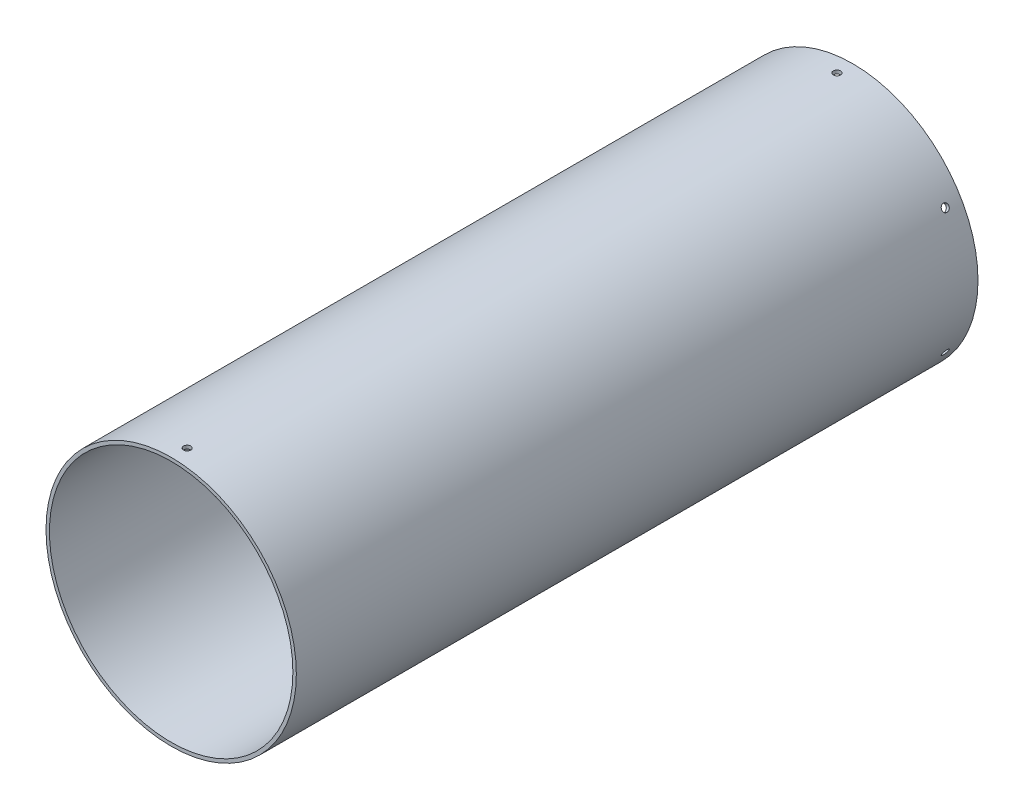
SolidWorks part; units mm, degrees
material "A-Glass Fiber"
ref_plane "Front Plane" through (0, 0, 0) normal (0, 0, 1) x (1, 0, 0)
ref_plane "Top Plane" through (0, 0, 0) normal (0, 1, 0) x (1, 0, 0)
ref_plane "Right Plane" through (0, 0, 0) normal (1, 0, 0) x (0, 0, -1)
sketch "Sketch1" plane through (0, 0, 0) normal (0, 0, 1) x (1, 0, 0)
  circle A0 centre (0, 0) radius 76.2
  circle A1 centre (0, 0) radius 78.359
  dimension "D1" = 156.718
  dimension "D2" = 152.4
extrude "Boss-Extrude1" add sketch "Sketch1" along normal blind 426.75
sketch "Sketch4" plane through (0, 0, 0) normal (0, 1, 0) x (1, 0, 0)
  line L0 (78.359, 0) -> (-78.359, 0) construction
  point P0 (0, -10)
  dimension "D1" = 10
hole_wizard "M4 Clearance Hole2" positions "Sketch4" profile "Sketch5" hole size "M4" standard "ANSI Metric"
sketch "Sketch5" plane through (0, 0, 10) normal (1, 0, 0) x (0, 0, 1)
  line L0 (0, 0) -> (0, 78.359)
  line L1 (0, 78.359) -> (2.25, 78.359)
  line L2 (2.25, 78.359) -> (2.25, 0)
  line L5 (2.25, 0) -> (0, 0)
  line L11 (0, -6.35) -> (0, 107.95) construction
  dimension "Thru Hole Dia." = 4.5
  dimension "Thru Hole Depth" = 78.359
pattern_circular "CirPattern1" count 6 over 360 about axis through (0, 0, 426.75) along (0, 0, -1) of "M4 Clearance Hole2"
sketch "Sketch6" plane through (0, 0, 0) normal (0, 1, 0) x (1, 0, 0)
  line L0 (-78.359, -426.75) -> (78.359, -426.75) construction
  point P0 (0, -416.75)
  dimension "D1" = 10
hole_wizard "M4 Clearance Hole3" positions "Sketch6" profile "Sketch7" hole size "M4" standard "ANSI Metric"
sketch "Sketch7" plane through (0, 0, 416.75) normal (1, 0, 0) x (0, 0, -1)
  line L0 (0, 0) -> (0, 78.359)
  line L1 (0, 78.359) -> (2.25, 78.359)
  line L2 (2.25, 78.359) -> (2.25, 0)
  line L5 (2.25, 0) -> (0, 0)
  line L11 (0, -6.35) -> (0, 107.95) construction
  dimension "Thru Hole Dia." = 4.5
  dimension "Thru Hole Depth" = 78.359
